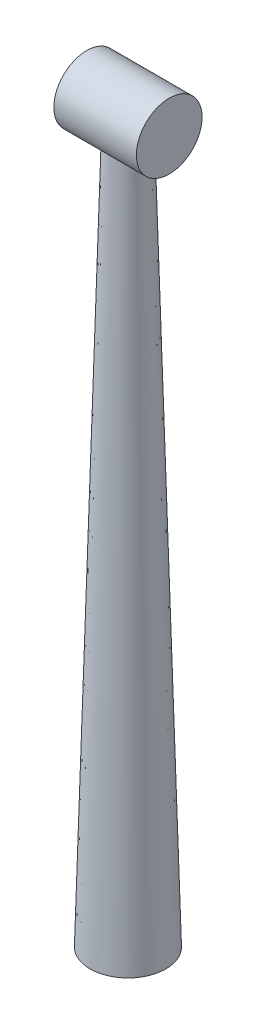
SolidWorks part; units mm, degrees
ref_plane "前视基准面" through (0, 0, 0) normal (0, 0, 1) x (1, 0, 0)
ref_plane "上视基准面" through (0, 0, 0) normal (0, 1, 0) x (1, 0, 0)
ref_plane "右视基准面" through (0, 0, 0) normal (1, 0, 0) x (0, 0, -1)
sketch "草图1" plane through (0, 0, 0) normal (1, 0, 0) x (0, 0, -1)
  circle A0 centre (0, 0) radius 3.985
  dimension "D1" = 7.97
extrude "凸台-拉伸1" add sketch "草图1" along normal blind 10
sketch "草图2" plane through (0, 0, 0) normal (0, 0, 1) x (1, 0, 0)
  line L0 (5, 0) -> (5, -87.6) construction
  line L1 (0, 3.985) -> (0, -3.985) construction
  line L2 (5, 0) -> (7.2171, 0)
  line L3 (7.2171, 0) -> (9.59, -87.6)
  line L4 (9.59, -87.6) -> (5, -87.6)
  line L5 (5, 0) -> (5, -87.6)
  dimension "D1" = 87.6
  dimension "D2" = 5
revolve "旋转1" add sketch "草图2" angle 360 about L0
